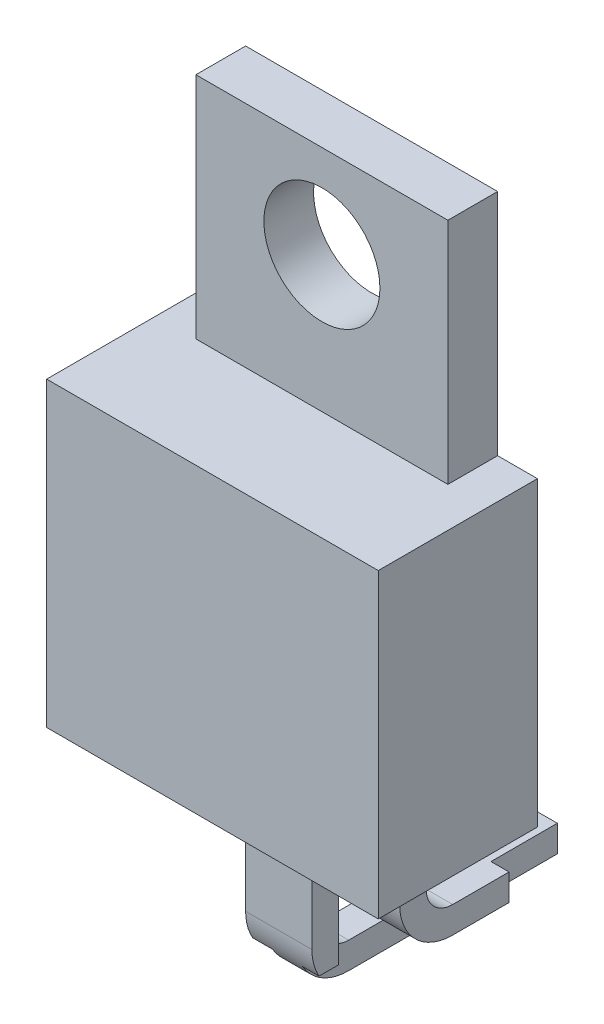
SolidWorks part; units mm, degrees
ref_plane "Спереди" through (0, 0, 0) normal (0, 0, 1) x (1, 0, 0)
ref_plane "Сверху" through (0, 0, 0) normal (0, 1, 0) x (1, 0, 0)
ref_plane "Справа" through (0, 0, 0) normal (1, 0, 0) x (0, 0, -1)
sketch "Эскиз1" plane through (0, 0, 0) normal (0, 0, 1) x (1, 0, 0)
  line L0 (0, 29.0506) -> (0, -32.0085) construction
  line L1 (-19.6488, 0) -> (24.5082, 0) construction
  line L2 (-3.8, 2.8) -> (-3.8, -4.1)
  line L3 (-5, -13.2) -> (5, -13.2)
  line L4 (-5, -13.2) -> (-5, -4.1)
  line L5 (-3.8, 2.8) -> (3.8, 2.8)
  line L6 (5, -13.2) -> (5, -4.1)
  line L7 (-3.8, -4.1) -> (-5, -4.1)
  line L8 (3.8, 2.8) -> (3.8, -4.1)
  line L9 (3.8, -4.1) -> (5, -4.1)
  circle A0 centre (0, 0) radius 1.75
  dimension "D1" = 3.5
  dimension "D2" = 2.8
  dimension "D3" = 10
  dimension "D5" = 6.9
  dimension "D6" = 1.2
extrude "Вытянуть1" add sketch "Эскиз1" along normal blind 4.8
sketch "Эскиз2" plane through (0, 0, 4.8) normal (0, 0, 1) x (1, 0, 0)
  line L0 (5, -4.1) -> (3.8, -4.1) construction
  line L1 (-6.1695, -4.1) -> (6.1449, -4.1)
  line L2 (-6.1695, -4.1) -> (-6.1695, 2.8069)
  line L3 (-6.1695, 2.8069) -> (6.1449, 2.8069)
  line L4 (6.1449, -4.1) -> (6.1449, 2.8069)
extrude "Вырез-Вытянуть1" cut sketch "Эскиз2" against normal offset from surface (3.3 mm away) 1.5 up to face at (0, -4.65, 0)
sketch "Эскиз3" plane through (0, -13.2, 0) normal (0, -1, 0) x (1, 0, 0)
  line L0 (0, 5.8129) -> (0, -0.7755) construction
  line L1 (-5.3656, 2.4) -> (5.2588, 2.4) construction
  line L2 (-5, 4.8) -> (5, 4.8) construction
  line L3 (-5, 0) -> (5, 0) construction
  line L4 (-5, 4.8) -> (-5, 0) construction
  line L5 (5, 4.8) -> (5, 0) construction
  line L7 (-1, 2) -> (1, 2)
  line L8 (-1, 2) -> (-1, 2.8)
  line L9 (-1, 2.8) -> (1, 2.8)
  line L10 (1, 2) -> (1, 2.8)
  line L11 (-3.6443, 2) -> (-1.6443, 2)
  line L12 (-3.6443, 2) -> (-3.6443, 2.8)
  line L13 (-3.6443, 2.8) -> (-1.6443, 2.8)
  line L14 (-1.6443, 2) -> (-1.6443, 2.8)
  line L15 (1.6443, 2) -> (3.6443, 2)
  line L16 (1.6443, 2) -> (1.6443, 2.8)
  line L17 (1.6443, 2.8) -> (3.6443, 2.8)
  line L18 (3.6443, 2) -> (3.6443, 2.8)
  dimension "D1" = 2
  dimension "D2" = 2
  dimension "D3" = 2
  dimension "D4" = 0.8
extrude "Вытянуть2" add sketch "Эскиз3" along normal blind 5
sketch "Эскиз4" plane through (0, -18.2, 0) normal (0, -1, 0) x (1, 0, 0)
  line L4 (1.6443, 2.8) -> (1.6443, 2)
  line L5 (1.6443, 2) -> (3.6443, 2)
  line L6 (3.6443, 2) -> (3.6443, 2.8)
  line L7 (3.6443, 2.8) -> (1.6443, 2.8)
  line L8 (1.6443, 2.8) -> (1.6443, 2)
  line L9 (1.6443, 2) -> (3.6443, 2)
  line L10 (3.6443, 2) -> (3.6443, 2.8)
  line L11 (3.6443, 2.8) -> (1.6443, 2.8)
  line L12 (-3.6443, 2.8) -> (-3.6443, 2)
  line L13 (-3.6443, 2) -> (-1.6443, 2)
  line L14 (-1.6443, 2) -> (-1.6443, 2.8)
  line L15 (-1.6443, 2.8) -> (-3.6443, 2.8)
  line L16 (-3.6443, 2.8) -> (-3.6443, 2)
  line L17 (-3.6443, 2) -> (-1.6443, 2)
  line L18 (-1.6443, 2) -> (-1.6443, 2.8)
  line L19 (-1.6443, 2.8) -> (-3.6443, 2.8)
  dimension "D1" = 0
  dimension "D2" = 0
extrude "Вырез-Вытянуть2" cut sketch "Эскиз4" against normal blind 2.5
sketch "Эскиз5" plane through (0, 0, 2) normal (0, 0, -1) x (-1, 0, 0)
  line L0 (0, -18.6315) -> (0, -12.2677) construction
  line L1 (1.6443, -15.7) -> (-5.1232, -15.7) construction
  line L2 (0, -18.2) -> (4.3997, -18.2) construction
  line L3 (1, -18.2) -> (-1, -18.2) construction
  line L4 (3.6443, -15.7) -> (3.6443, -13.2) construction
  line L5 (-0.506, -18.6) -> (0.4053, -18.6)
  line L6 (-0.506, -18.6) -> (-0.506, -17.8)
  line L7 (-0.506, -17.8) -> (0.4053, -17.8)
  line L8 (0.4053, -18.6) -> (0.4053, -17.8)
  line L9 (1.6443, -16.1) -> (3.6443, -16.1)
  line L10 (1.6443, -16.1) -> (1.6443, -15.3)
  line L11 (1.6443, -15.3) -> (3.6443, -15.3)
  line L12 (3.6443, -16.1) -> (3.6443, -15.3)
  line L13 (-1.6443, -15.7) -> (-1.6443, -13.2) construction
  line L14 (-3.6443, -16.1) -> (-1.6443, -16.1)
  line L15 (-3.6443, -16.1) -> (-3.6443, -15.3)
  line L16 (-3.6443, -15.3) -> (-1.6443, -15.3)
  line L17 (-1.6443, -16.1) -> (-1.6443, -15.3)
  line L18 (-3.6443, -15.7) -> (-3.6443, -13.2) construction
  line L19 (1.6443, -15.7) -> (1.6443, -13.2) construction
  dimension "D1" = 0.8
extrude "Вытянуть3" add sketch "Эскиз5" along normal blind 2.5 and the other way up to surface other way up to face at (-2.6443, -14.45, 2.8)
sketch "Эскиз6" plane through (0, -18.2, 0) normal (0, -1, 0) x (1, 0, 0)
  line L4 (1, 2.8) -> (0.506, 2.8)
  line L5 (0.506, 2.8) -> (0.506, 2)
  line L6 (0.506, 2) -> (1, 2)
  line L7 (1, 2) -> (1, 2.8)
  line L8 (1, 2.8) -> (0.506, 2.8)
  line L9 (0.506, 2.8) -> (0.506, 2)
  line L10 (0.506, 2) -> (1, 2)
  line L11 (1, 2) -> (1, 2.8)
  line L12 (-1, 2) -> (-0.4053, 2)
  line L13 (-0.4053, 2) -> (-0.4053, 2.8)
  line L14 (-0.4053, 2.8) -> (-1, 2.8)
  line L15 (-1, 2.8) -> (-1, 2)
  line L16 (-1, 2) -> (-0.4053, 2)
  line L17 (-0.4053, 2) -> (-0.4053, 2.8)
  line L18 (-0.4053, 2.8) -> (-1, 2.8)
  line L19 (-1, 2.8) -> (-1, 2)
  dimension "D1" = 0
  dimension "D2" = 0
extrude "Вырез-Вытянуть3" cut sketch "Эскиз6" against normal blind 0.4
fillet "Скругление1" radius 0.8 3 edges at (0.0504, -17.8, 2) (-2.6443, -15.3, 2) (2.6443, -15.3, 2)
fillet "Скругление2" radius 1.6 3 edges at (-2.6443, -16.1, 2.8) (0.0504, -18.6, 2.8) (2.6443, -16.1, 2.8)
sketch "Эскиз7" plane through (0, 0, -0.5) normal (0, 0, -1) x (-1, 0, 0)
  line L0 (-2.6443, -13.6506) -> (-2.6443, -17.1658) construction
  line L1 (2.6443, -13.6506) -> (2.6443, -17.9177) construction
  line L2 (1.6443, -15.3) -> (1.6443, -16.1) construction
  line L3 (3.6443, -16.1) -> (3.6443, -15.3) construction
  line L4 (-0.506, -17.8) -> (-0.506, -18.6)
  line L5 (-0.506, -18.6) -> (0.4053, -18.6)
  line L6 (0.4053, -18.6) -> (0.4053, -17.8)
  line L7 (0.4053, -17.8) -> (-0.506, -17.8)
  line L8 (-0.506, -17.8) -> (-0.506, -18.6)
  line L9 (-0.506, -18.6) -> (0.4053, -18.6)
  line L10 (0.4053, -18.6) -> (0.4053, -17.8)
  line L11 (0.4053, -17.8) -> (-0.506, -17.8)
  line L12 (-3.6443, -15.3) -> (-3.6443, -16.1) construction
  line L13 (-1.6443, -16.1) -> (-1.6443, -15.3) construction
  line L14 (-3.6443, -16.1) -> (-1.6443, -16.1) construction
  line L15 (-3.1, -16.1) -> (-2.1887, -16.1)
  line L16 (-3.1, -16.1) -> (-3.1, -15.3)
  line L17 (-3.1, -15.3) -> (-2.1887, -15.3)
  line L18 (-2.1887, -16.1) -> (-2.1887, -15.3)
  line L19 (-1.6443, -15.3) -> (-3.6443, -15.3) construction
  line L20 (1.6443, -16.1) -> (3.6443, -16.1) construction
  line L21 (2.1887, -16.1) -> (3.1, -16.1)
  line L22 (2.1887, -16.1) -> (2.1887, -15.3)
  line L23 (2.1887, -15.3) -> (3.1, -15.3)
  line L24 (3.1, -16.1) -> (3.1, -15.3)
  line L25 (3.6443, -15.3) -> (1.6443, -15.3) construction
  dimension "D1" = 0
extrude "Вытянуть4" add sketch "Эскиз7" along normal blind 2
